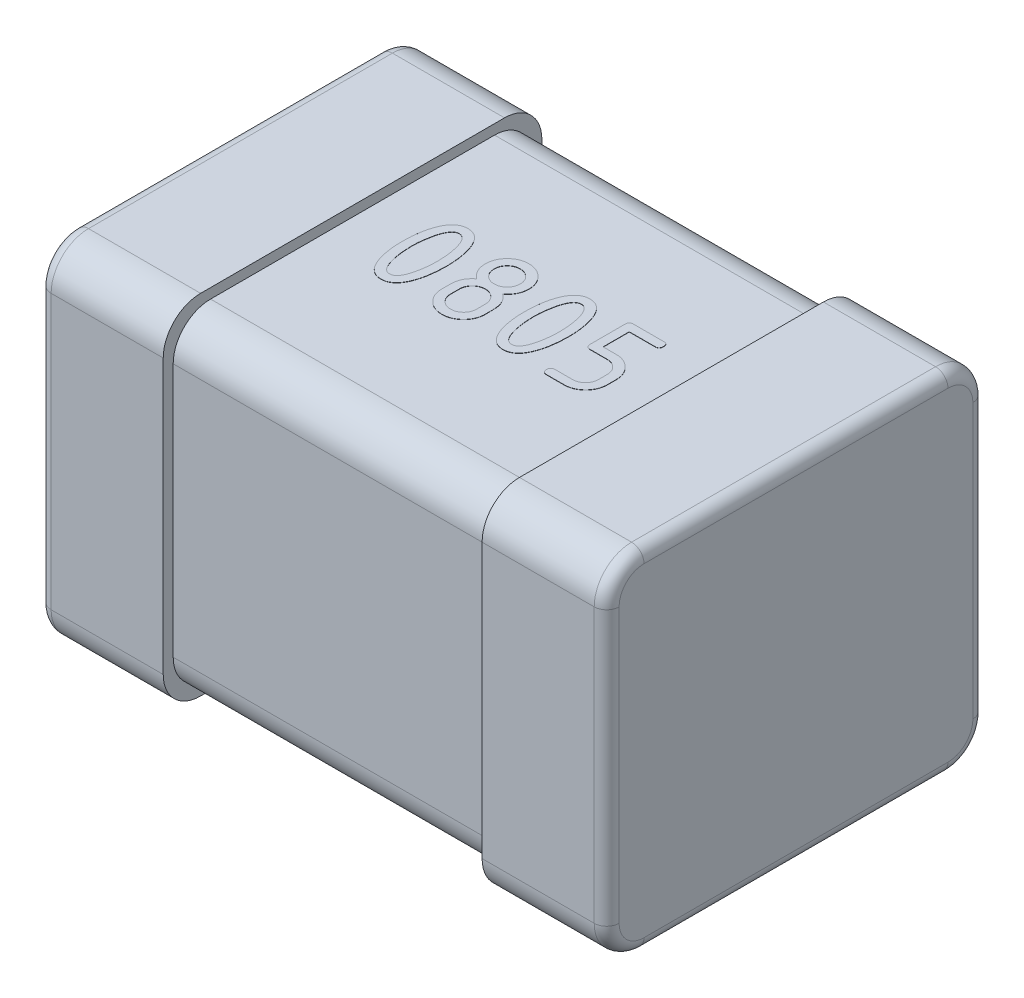
SolidWorks part; units mm, degrees
ref_plane "Front" through (0, 0, 0) normal (0, 0, 1) x (1, 0, 0)
ref_plane "Top" through (0, 0, 0) normal (0, 1, 0) x (1, 0, 0)
ref_plane "Right" through (0, 0, 0) normal (1, 0, 0) x (0, 0, -1)
sketch "Sketch1" plane through (0, 0, 0) normal (0, 1, 0) x (1, 0, 0)
  line L1 (-1.14, -0.76) -> (1.14, -0.76)
  line L2 (-1.14, -0.76) -> (-1.14, 0.76)
  line L3 (-1.14, 0.76) -> (1.14, 0.76)
  line L4 (1.14, -0.76) -> (1.14, 0.76)
  line L5 (-1.14, -0.76) -> (1.14, 0.76) construction
  line L6 (-1.14, 0.76) -> (1.14, -0.76) construction
  point P0 (0, 0)
  dimension "D1" = 1.52
  dimension "D2" = 2.28
extrude "Boss-Extrude1" add sketch "Sketch1" along normal mid plane 1.4
sketch "Sketch3" plane through (0, 0, 0) normal (1, 0, 0) x (0, 0, -1)
  line L8 (-0.72, -0.66) -> (0.72, -0.66)
  line L9 (0.72, -0.66) -> (0.72, 0.66)
  line L10 (0.72, 0.66) -> (-0.72, 0.66)
  line L11 (-0.72, 0.66) -> (-0.72, -0.66)
  line L12 (-0.72, -0.66) -> (0.72, -0.66)
  line L13 (0.72, -0.66) -> (0.72, 0.66)
  line L14 (0.72, 0.66) -> (-0.72, 0.66)
  line L15 (-0.72, 0.66) -> (-0.72, -0.66)
  dimension "D1" = 0.04
extrude "Cut-Extrude1" cut sketch "Sketch3" against normal offset from surface 0.5 and the other way offset from surface (0.64 mm away) 0.5 flip side to cut up to face at (-1.14, 0, 0) other way up to face at (1.14, 0, 0)
fillet "Fillet1" radius 0.15 4 edges at (0, -0.66, -0.72) (0, 0.66, -0.72) (0, -0.66, 0.72) (0, 0.66, 0.72)
fillet "Fillet2" radius 0.15 8 edges at (-0.89, -0.7, 0.76) (-0.89, 0.7, 0.76) (0.89, 0.7, 0.76) (0.89, -0.7, 0.76) (-0.89, -0.7, -0.76) (-0.89, 0.7, -0.76) (0.89, 0.7, -0.76) (0.89, -0.7, -0.76)
fillet "Fillet3" radius 0.05 16 edges at (1.14, 0.6561, -0.7161) (1.14, 0, -0.76) (1.14, -0.6561, -0.7161) (1.14, -0.7, 0) (1.14, -0.6561, 0.7161) (1.14, 0, 0.76) (1.14, 0.6561, 0.7161) (1.14, 0.7, 0) (-1.14, -0.6561, -0.7161) (-1.14, 0, -0.76) (-1.14, 0.6561, -0.7161) (-1.14, 0.7, 0) (-1.14, 0.6561, 0.7161) (-1.14, 0, 0.76) (-1.14, -0.6561, 0.7161) (-1.14, -0.7, 0)
sketch "Sketch4" plane through (0, 0.66, 0) normal (0, 1, 0) x (1, 0, 0)
  line L0 (-0.64, -0.1592) -> (0.64, -0.1592) construction
  line L1 (-0.64, -0.57) -> (-0.64, 0.57) construction
  line L2 (0.64, -0.61) -> (0.64, 0.61) construction
  text T0 "0805" font "@Adobe Fan Heiti Std B" height 0.35
extrude "Boss-Extrude2" add sketch "Sketch4" along normal blind 0.001
